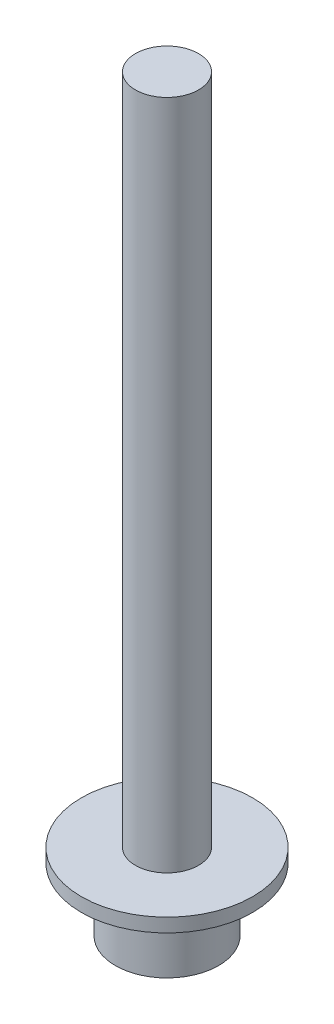
SolidWorks part; units mm, degrees
ref_plane "Front Plane" through (0, 0, 0) normal (0, 0, 1) x (1, 0, 0)
ref_plane "Top Plane" through (0, 0, 0) normal (0, 1, 0) x (1, 0, 0)
ref_plane "Right Plane" through (0, 0, 0) normal (1, 0, 0) x (0, 0, -1)
sketch "Sketch1" plane through (-24.4127, 0, -3.433) normal (0.9903, 0, 0.1393) x (0.1393, 0, -0.9903)
  line L0 (12.1136, -0.7854) -> (8.6084, -0.7854) construction
  line L1 (12.1136, -38.8854) -> (12.1136, -0.7854) construction
  line L2 (13.2312, -38.8854) -> (7.4908, -38.8854) construction
  line L3 (8.6084, -38.8854) -> (8.6084, -0.7854) construction
  line L4 (13.2312, -38.8854) -> (13.2312, -42.3906) construction
  line L5 (7.4908, -38.8854) -> (7.4908, -42.3906) construction
  line L6 (13.2312, -42.3906) -> (7.4908, -42.3906) construction
  line L7 (12.1136, -0.7854) -> (8.6084, -0.7854)
  line L8 (12.1136, -38.8854) -> (12.1136, -0.7854)
  line L9 (13.2312, -38.8854) -> (7.4908, -38.8854)
  line L10 (8.6084, -38.8854) -> (8.6084, -0.7854)
  line L11 (13.2312, -38.8854) -> (13.2312, -42.3906)
  line L12 (7.4908, -38.8854) -> (7.4908, -42.3906)
  line L13 (13.2312, -42.3906) -> (7.4908, -42.3906)
  line L14 (12.1136, -38.8854) -> (8.6084, -38.8854) construction
  line L15 (12.1136, -38.8854) -> (8.6084, -38.8854)
  line L16 (10.361, -42.3906) -> (10.361, -0.7854) construction
  line L17 (15.1235, -38.8854) -> (15.1235, -38.1234) construction
  line L18 (15.1235, -38.1234) -> (5.5985, -38.1234) construction
  line L19 (5.5985, -38.8854) -> (5.5985, -38.1234) construction
  line L20 (15.1235, -38.8854) -> (5.5985, -38.8854) construction
  line L21 (15.1235, -38.8854) -> (15.1235, -38.1234)
  line L22 (15.1235, -38.1234) -> (5.5985, -38.1234)
  line L23 (5.5985, -38.8854) -> (5.5985, -38.1234)
  line L24 (15.1235, -38.8854) -> (5.5985, -38.8854)
revolve "Revolve1" add sketch "Sketch1" angle 360 about L16
